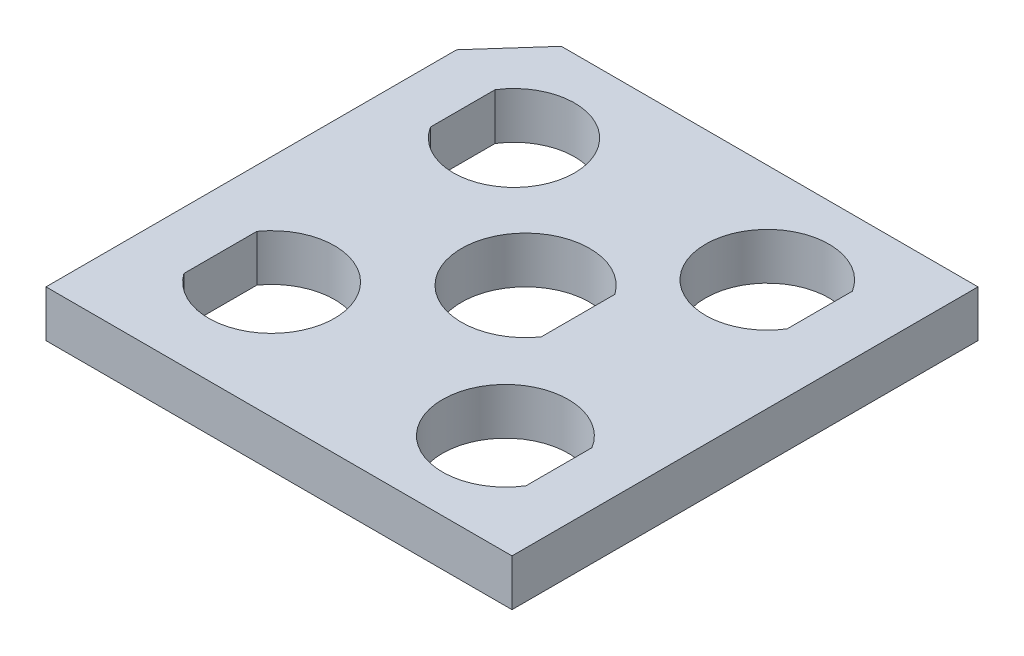
SolidWorks part; units mm, degrees
ref_plane "Plano frontal" through (0, 0, 0) normal (0, 0, 1) x (1, 0, 0)
ref_plane "Plano superior" through (0, 0, 0) normal (0, 1, 0) x (1, 0, 0)
ref_plane "Plano direito" through (0, 0, 0) normal (1, 0, 0) x (0, 0, -1)
sketch "Esboço1" plane through (0, 0, 0) normal (0, 1, 0) x (1, 0, 0)
  line L0 (0, 0) -> (0, 20)
  line L1 (0, 0) -> (20, 0)
  line L2 (0, 20) -> (20, 20)
  line L3 (20, 20) -> (20, 0)
extrude "Ressalto-extrusão3" add sketch "Esboço1" along normal blind 2
sketch "Esboço5" plane through (0, 2, 0) normal (0, 1, 0) x (1, 0, 0)
  line L0 (2.3093, 16.9627) -> (2.3093, 14.1914)
  line L1 (2.4617, 3.456) -> (2.4617, 6.5865)
  line L2 (17.4651, 14.3414) -> (17.4651, 17.1414)
  line L3 (12.4861, 11.928) -> (12.4861, 8.7657)
  line L4 (17.6939, 5.7383) -> (17.6939, 2.9098)
  line L5 (3.125, 21.1301) -> (-1.5139, 15.9231)
  line L6 (-1.5139, 15.9231) -> (-4.1838, 19.8285)
  line L7 (-4.1838, 19.8285) -> (-3.3828, 21.7308)
  line L8 (-3.3828, 21.7308) -> (3.125, 21.1301)
  arc A0 (2.3093, 14.1914) -> (2.3093, 16.9627) centre (4.5093, 15.5771) ccw
  arc A1 (17.4651, 17.1414) -> (17.4651, 14.3414) centre (15.2151, 15.7414) ccw
  arc A2 (2.4617, 3.456) -> (2.4617, 6.5865) centre (4.6617, 5.0212) ccw
  arc A3 (17.6939, 5.7383) -> (17.6939, 2.9098) centre (15.3939, 4.3241) ccw
  arc A4 (12.4861, 11.928) -> (12.4861, 8.7657) centre (10.2361, 10.3469) ccw
  point P17 (0, 0)
  point P20 (0, 0)
extrude "Corte-extrusão5" cut sketch "Esboço5" against normal through all
